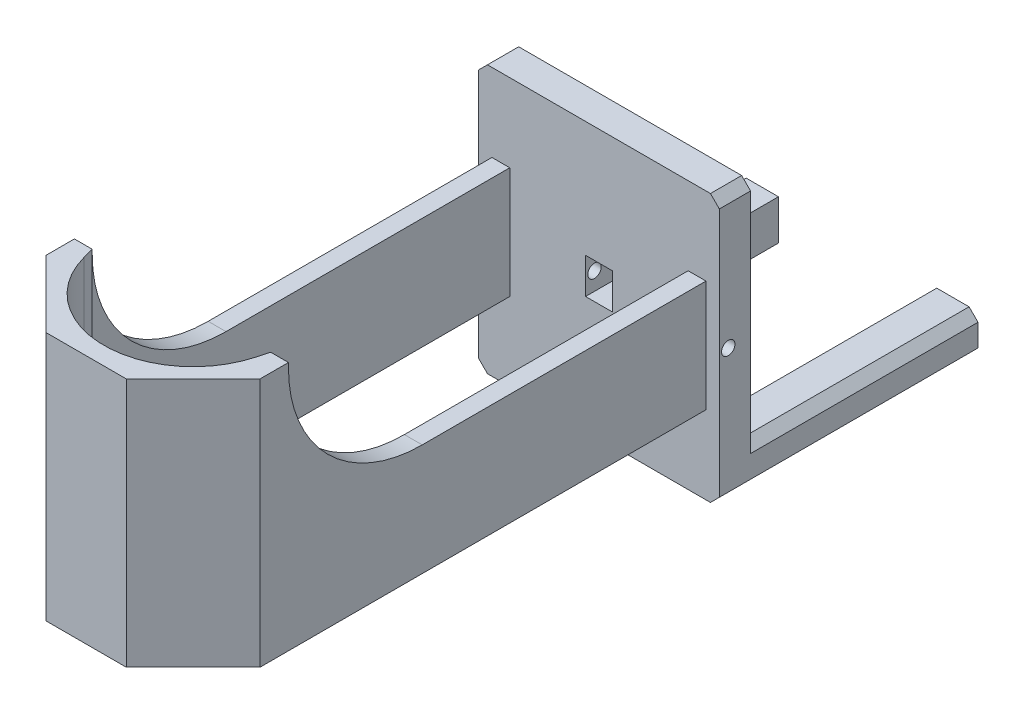
SolidWorks part; units mm, degrees
ref_plane "Front Plane" through (0, 0, 0) normal (0, 0, 1) x (1, 0, 0)
ref_plane "Top Plane" through (0, 0, 0) normal (0, 1, 0) x (1, 0, 0)
ref_plane "Right Plane" through (0, 0, 0) normal (1, 0, 0) x (0, 0, -1)
sketch "Sketch1" plane through (0, 0, 0) normal (0, 0, 1) x (1, 0, 0)
  line L0 (54, 2) -> (54, 7) construction
  line L1 (54, 7) -> (52, 9) construction
  line L2 (52, 9) -> (44.75, 9) construction
  line L3 (44.75, 9) -> (44.75, 0) construction
  line L4 (44.75, 0) -> (52, 0) construction
  line L5 (52, 0) -> (54, 2) construction
  line L6 (0, 7) -> (0, 2) construction
  line L7 (0, 2) -> (2, 0) construction
  line L8 (2, 0) -> (9.25, 0) construction
  line L9 (9.25, 0) -> (9.25, 9) construction
  line L10 (9.25, 9) -> (2, 9) construction
  line L11 (2, 9) -> (0, 7) construction
  line L12 (37.6, 51) -> (52, 51) construction
  line L13 (52, 51) -> (54, 53) construction
  line L14 (54, 53) -> (54, 58) construction
  line L15 (54, 58) -> (52, 60) construction
  line L16 (52, 60) -> (2, 60) construction
  line L17 (2, 60) -> (0, 58) construction
  line L18 (0, 58) -> (0, 53) construction
  line L19 (0, 53) -> (2, 51) construction
  line L20 (2, 51) -> (16.4, 51) construction
  line L21 (16.4, 51) -> (37.6, 51) construction
  line L22 (54, 2) -> (54, 7)
  line L23 (54, 7) -> (52, 9)
  line L24 (52, 9) -> (44.75, 9)
  line L25 (44.75, 9) -> (44.75, 0)
  line L26 (44.75, 0) -> (52, 0)
  line L27 (52, 0) -> (54, 2)
  line L28 (0, 7) -> (0, 2)
  line L29 (0, 2) -> (2, 0)
  line L30 (2, 0) -> (9.25, 0)
  line L31 (9.25, 0) -> (9.25, 9)
  line L32 (9.25, 9) -> (2, 9)
  line L33 (2, 9) -> (0, 7)
  line L34 (37.6, 51) -> (52, 51)
  line L35 (52, 51) -> (54, 53)
  line L36 (54, 53) -> (54, 58)
  line L37 (54, 58) -> (52, 60)
  line L38 (52, 60) -> (2, 60)
  line L39 (2, 60) -> (0, 58)
  line L40 (0, 58) -> (0, 53)
  line L41 (0, 53) -> (2, 51)
  line L42 (2, 51) -> (16.4, 51)
  line L43 (16.4, 51) -> (37.6, 51)
extrude "Boss-Extrude1" add sketch "Sketch1" along normal blind 5 contours L38 L39 L40 L41 L42 L43 L34 L35 L36 L37
sketch "Sketch2" plane through (0, 0, -51) normal (0, 0, 1) x (1, 0, 0)
  line L0 (0, 7) -> (0, 2) construction
  line L1 (0, 2) -> (2, 0) construction
  line L2 (2, 0) -> (9.25, 0) construction
  line L3 (9.25, 0) -> (9.25, 9) construction
  line L4 (9.25, 9) -> (2, 9) construction
  line L5 (2, 9) -> (0, 7) construction
  line L6 (54, 2) -> (54, 7) construction
  line L7 (54, 7) -> (52, 9) construction
  line L8 (52, 9) -> (44.75, 9) construction
  line L9 (44.75, 9) -> (44.75, 0) construction
  line L10 (44.75, 0) -> (52, 0) construction
  line L11 (52, 0) -> (54, 2) construction
  line L12 (0, 7) -> (0, 2)
  line L13 (0, 2) -> (2, 0)
  line L14 (2, 0) -> (9.25, 0)
  line L15 (9.25, 0) -> (9.25, 9)
  line L16 (9.25, 9) -> (2, 9)
  line L17 (2, 9) -> (0, 7)
  line L18 (54, 2) -> (54, 7)
  line L19 (54, 7) -> (52, 9)
  line L20 (52, 9) -> (44.75, 9)
  line L21 (44.75, 9) -> (44.75, 0)
  line L22 (44.75, 0) -> (52, 0)
  line L23 (52, 0) -> (54, 2)
extrude "Boss-Extrude2" add sketch "Sketch2" along normal blind 56 separate body
sketch "Sketch8" plane through (0, 0, 5) normal (0, 0, 1) x (1, 0, 0)
  line L0 (0, 2) -> (0, 58)
  line L1 (2, 60) -> (52, 60)
  line L2 (54, 58) -> (54, 2)
  line L3 (52, 0) -> (2, 0)
  line L4 (52, 60) -> (2, 60) construction
  line L5 (54, 53) -> (54, 58) construction
  line L6 (0, 58) -> (2, 60)
  line L7 (52, 60) -> (54, 58)
  line L8 (54, 2) -> (52, 0)
  line L9 (2, 0) -> (0, 2)
  point P0 (0, 0)
  point P1 (0, 60)
  point P4 (54, 60)
  point P5 (54, 0)
  dimension "D1" = 0
  dimension "D2" = 0
extrude "Boss-Extrude3" add sketch "Sketch8" along normal blind 2 and the other way blind 5
sketch "Sketch9" plane through (0, 0, 7) normal (0, 0, 1) x (1, 0, 0)
  line L1 (24, 34) -> (30, 34)
  line L2 (24, 34) -> (24, 26)
  line L3 (24, 26) -> (30, 26)
  line L4 (30, 34) -> (30, 26)
  line L5 (24, 34) -> (30, 26) construction
  line L6 (24, 26) -> (30, 34) construction
  point P0 (27, 30)
  dimension "D1" = 8
  dimension "D2" = 6
  dimension "D3" = 27
  dimension "D4" = 30
extrude "Cut-Extrude3" cut sketch "Sketch9" against normal blind 6
sketch "Sketch10" plane through (30, 0, 0) normal (-1, 0, 0) x (0, 0, 1)
  line L0 (7, 58) -> (7, 2) construction
  circle A0 centre (5, 30) radius 1.5
  dimension "D1" = 3
  dimension "D2" = 2
  dimension "D3" = 30
extrude "Cut-Extrude4" cut sketch "Sketch10" against normal through all both and the other way through all
sketch "Sketch3" plane through (0, 0, -51) normal (0, 0, 1) x (1, 0, 0)
  circle A0 centre (4.5, 4.5) radius 2.15
  circle A1 centre (4.5, 55.5) radius 2.15
  circle A2 centre (49.5, 55.5) radius 2.15
  circle A3 centre (49.5, 4.5) radius 2.15
  circle A4 centre (4.5, 24.5) radius 2.15
  circle A5 centre (49.5, 24.5) radius 2.15
  dimension "D1" = 4.3
  dimension "D2" = 4.3
  dimension "D3" = 4.3
  dimension "D4" = 4.3
  dimension "D13" = 4.3
  dimension "D14" = 4.3
  dimension "D5" = 51
  dimension "D6" = 0
  dimension "D7" = 45
  dimension "D8" = 51
  dimension "D9" = 45
  dimension "D10" = 0
  dimension "D11" = 4.5
  dimension "D12" = 4.5
  dimension "D15" = 31
  dimension "D16" = 0
  dimension "D17" = 0
  dimension "D18" = 0
sketch "Sketch5" plane through (0, 60, 0) normal (0, 1, 0) x (1, 0, 0)
  line L0 (32.6, 5) -> (21.4, 5)
  line L5 (37.6, 10) -> (37.6, 46)
  line L8 (37.6, 10) -> (32.6, 5)
  line L9 (27, 71.4989) -> (27, -28.5011) construction
  line L11 (16.4, 10) -> (21.4, 5)
  line L12 (16.4, 10) -> (16.4, 46)
  line L14 (16.4, 46) -> (37.6, 46)
sketch3d "3DSketch1" plane through (0, 0, 0) normal (0, 0, 1) x (1, 0, 0)
  dimension "D1" = 30
sketch3d "3DSketch2" plane through (0, 0, 0) normal (0, 0, 1) x (1, 0, 0)
  dimension "D1" = 27
sketch3d "3DSketch3" plane through (0, 0, 0) normal (0, 0, 1) x (1, 0, 0)
  dimension "D1" = 2
sketch "Sketch11" plane through (0, 30, 0) normal (0, 1, 0) x (1, 0, 0)
  line L0 (52, 56) -> (2, 56) construction
  line L2 (27, 71.4989) -> (27, -28.5011) construction
  line L3 (3, -7) -> (51, -7)
  line L4 (51, -7) -> (51, -122)
  line L5 (51, -122) -> (3, -122)
  line L6 (3, -122) -> (3, -7)
  line L8 (52, -7) -> (2, -7) construction
  circle A0 centre (27, -98) radius 20 construction
  dimension "D1" = 40
  dimension "D2" = 154
  dimension "D3" = 0
  dimension "D4" = 24
  dimension "D5" = 48
  dimension "D6" = 24
  dimension "D7" = 0
extrude "Boss-Extrude4" add sketch "Sketch11" along normal blind 43.5 and the other way blind 12.5 contours L4 L5 L6 L3
sketch "Sketch12" plane through (0, 73.5, 0) normal (0, 1, 0) x (1, 0, 0)
  line L0 (3, -122) -> (3, -7) construction
  line L1 (52, 56) -> (2, 56) construction
  line L2 (52, -7) -> (51, -7) construction
  line L4 (7, -100.633) -> (7, -7)
  line L5 (7, -7) -> (47, -7)
  line L6 (47, -100.633) -> (47, -7)
  line L7 (51, -7) -> (51, -122) construction
  line L8 (7.6815, -103.1764) -> (7, -100.633)
  line L9 (46.3185, -103.1764) -> (47, -100.633)
  line L10 (27, 71.4989) -> (27, -28.5011) construction
  arc A0 (7.6815, -103.1764) -> (46.3185, -103.1764) centre (27, -98) ccw
  dimension "D1" = 40
  dimension "D4" = 0
  dimension "D8" = 0
  dimension "D2" = 24
  dimension "D3" = 154
  dimension "D5" = 4
  dimension "D6" = 4
  dimension "D9" = 15
extrude "Cut-Extrude5" cut sketch "Sketch12" against normal through all
sketch "Sketch13" plane through (27, 0, 0) normal (1, 0, 0) x (0, 0, -1)
  line L0 (-7, 73.5) -> (-122, 73.5) construction
  line L1 (-7, 42.5) -> (-70.633, 42.5)
  line L2 (-7, 42.5) -> (-7, 73.5)
  line L3 (-7, 73.5) -> (-100.633, 73.5)
  line L4 (-100.633, 72.5) -> (-100.633, 73.5)
  line L6 (-100.633, 17.5) -> (-100.633, 73.5) construction
  line L7 (-7, 17.5) -> (-122, 17.5) construction
  line L8 (-7, 58) -> (-7, 60) construction
  arc A0 (-100.633, 72.5) -> (-70.633, 42.5) centre (-70.633, 72.5) ccw
  dimension "D5" = 30
  dimension "D1" = 0
  dimension "D2" = 0
  dimension "D3" = 25
  dimension "D4" = 0
extrude "Cut-Extrude6" cut sketch "Sketch13" against normal through all both and the other way through all
chamfer "Chamfer1" distance 15 angle 45 1 edges at (3, 45.5, 122)
chamfer "Chamfer2" distance 15 angle 45 1 edges at (51, 45.5, 122)
